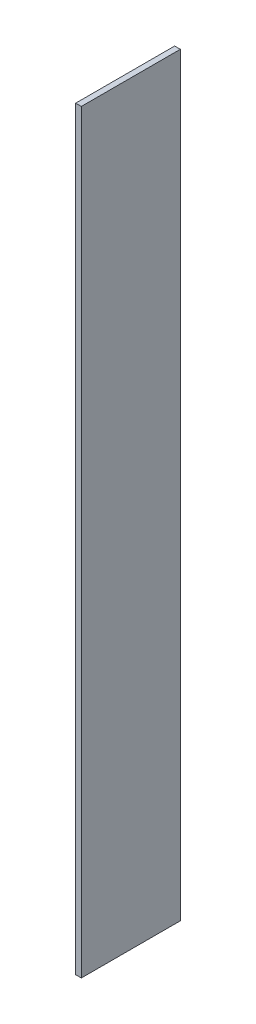
SolidWorks part; units mm, degrees
ref_plane "Спереди" through (0, 0, 0) normal (0, 0, 1) x (1, 0, 0)
ref_plane "Сверху" through (0, 0, 0) normal (0, 1, 0) x (1, 0, 0)
ref_plane "Справа" through (0, 0, 0) normal (1, 0, 0) x (0, 0, -1)
sketch "Эскиз1" plane through (0, 0, 0) normal (0, 1, 0) x (1, 0, 0)
  line L1 (1, 10.1482) -> (5, 10.1482)
  line L2 (1, 10.1482) -> (1, -59.7541)
  line L3 (1, -59.7541) -> (5, -59.7541)
  line L4 (5, 10.1482) -> (5, -59.7541)
  dimension "D1" = 4
extrude "Вытянуть1" add sketch "Эскиз1" along normal blind 533
